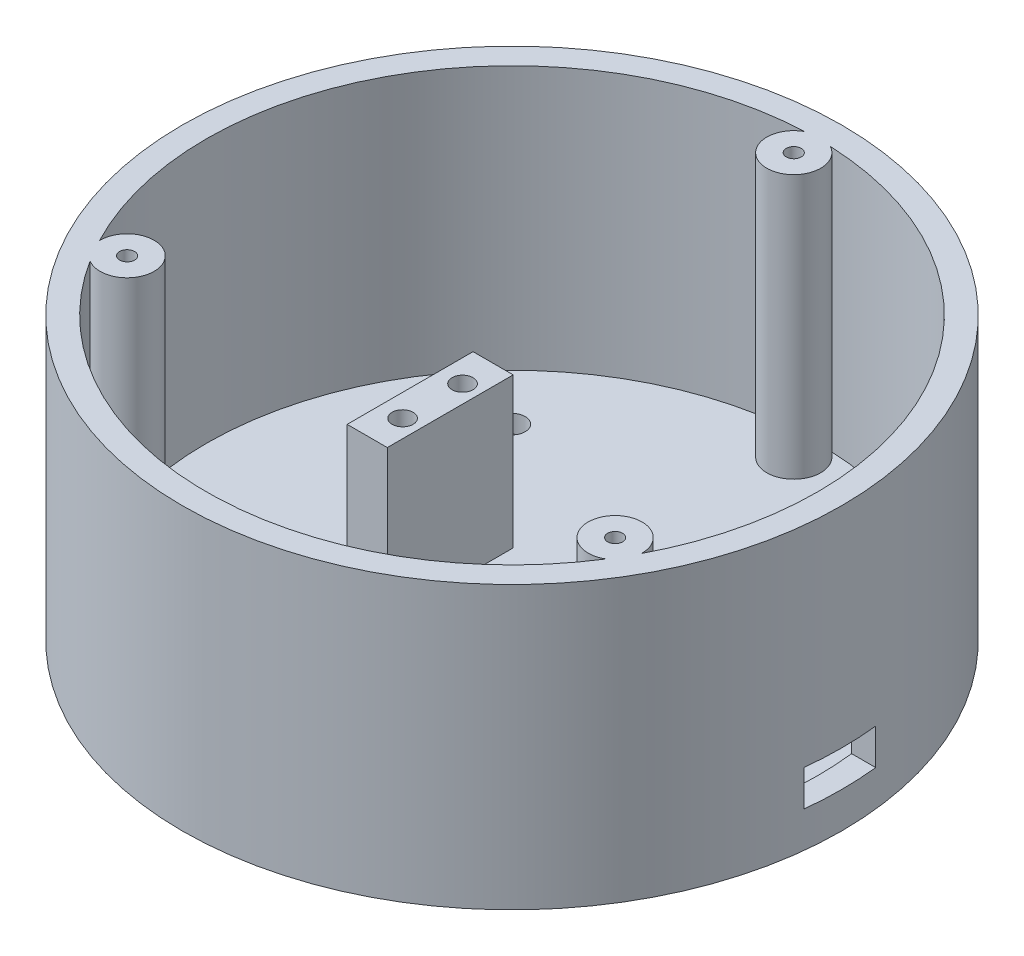
SolidWorks part; units mm, degrees
ref_plane "Piano frontale" through (0, 0, 0) normal (0, 0, 1) x (1, 0, 0)
ref_plane "Piano superiore" through (0, 0, 0) normal (0, 1, 0) x (1, 0, 0)
ref_plane "Piano destro" through (0, 0, 0) normal (1, 0, 0) x (0, 0, -1)
sketch "Schizzo1" plane through (0, 0, 0) normal (0, 1, 0) x (1, 0, 0)
  circle A0 centre (0, 0) radius 55
  dimension "D1" = 110
extrude "Estrusione-Estrusione1" add sketch "Schizzo1" along normal blind 47
sketch "Schizzo2" plane through (0, 47, 0) normal (0, 1, 0) x (1, 0, 0)
  circle A0 centre (0, 0) radius 51
  dimension "D1" = 102
extrude "Taglio-Estrusione1" cut sketch "Schizzo2" against normal blind 44
sketch "Schizzo3" plane through (0, 3, 0) normal (0, 1, 0) x (1, 0, 0)
  line L0 (-13.65, -10.5) -> (-13.65, 10.5) construction
  line L1 (-10.3, 10.5) -> (-17, 10.5)
  line L2 (-10.3, 10.5) -> (-10.3, -10.5)
  line L3 (-10.3, -10.5) -> (-17, -10.5)
  line L4 (-17, 10.5) -> (-17, -10.5)
  line L5 (-10.3, 0) -> (-17, 0) construction
  line L6 (0, -23.6186) -> (0, 49.8842) construction
  line L7 (34.65, 10.5) -> (34.65, -10.5) construction
  line L8 (31.3, 10.5) -> (38, 10.5)
  line L9 (31.3, 10.5) -> (31.3, -10.5)
  line L10 (31.3, -10.5) -> (38, -10.5)
  line L11 (38, 10.5) -> (38, -10.5)
  line L12 (31.3, 0) -> (38, 0) construction
  point P8 (-13.65, 0)
  point P20 (34.65, 0)
  point P21 (0, 49.8842)
  dimension "D1" = 13.65
  dimension "D2" = 6.7
  dimension "D3" = 21
  dimension "D4" = 34.65
  dimension "D5" = 21
  dimension "D6" = 6.7
extrude "Estrusione-Estrusione2" add sketch "Schizzo3" along normal blind 25
sketch "Schizzo9" plane through (0, 28, 0) normal (0, 1, 0) x (1, 0, 0)
  line L0 (0, -14.2526) -> (0, 18.3248) construction
  line L1 (0, 0) -> (-26.1637, 0) construction
  line L3 (0, 0) -> (42.8597, 0) construction
  circle A0 centre (-13.25, 5) radius 1.75
  circle A1 centre (-13.25, -5) radius 1.75
  circle A2 centre (34.25, 5) radius 1.75
  circle A3 centre (34.25, -5) radius 1.75
  point P5 (-13.0819, 0)
  dimension "D2" = 3.5
  dimension "D4" = 3.5
  dimension "D6" = 34.25
  dimension "D1" = 13.25
  dimension "D3" = 5
  dimension "D5" = 5
extrude "Taglio-Estrusione2" cut sketch "Schizzo9" against normal blind 12 contours A2 | A3 | A1 | A0
sketch "Schizzo10" plane through (0, 0, 0) normal (1, 0, 0) x (0, 0, -1)
  line L0 (0, 0) -> (0, 17.9146) construction
  line L1 (-6, 12) -> (6, 12)
  line L2 (-6, 12) -> (-6, 6)
  line L3 (-6, 6) -> (6, 6)
  line L4 (6, 12) -> (6, 6)
  line L5 (-55, 0) -> (55, 0) construction
  dimension "D1" = 12
  dimension "D2" = 6
  dimension "D3" = 6
  dimension "D4" = 6
extrude "Taglio-Estrusione3" cut sketch "Schizzo10" along normal blind 67 from offset 45
sketch "Schizzo12" plane through (0, 3, 0) normal (0, 1, 0) x (1, 0, 0)
  line L0 (0, 0) -> (0, 48.0517) construction
  line L1 (0, 0) -> (-46.6264, 0) construction
  circle A0 centre (-28.28, 28.28) radius 2.2
  circle A1 centre (28.28, 28.28) radius 2.2
  circle A2 centre (28.28, -28.28) radius 2.2
  circle A3 centre (-28.28, -28.28) radius 2.2
  point P14 (0, 0)
  dimension "D1" = 4.4
  dimension "D4" = 4
  dimension "D2" = 28.28
  dimension "D3" = 28.28
  dimension "D5" = 28.28
  dimension "D6" = 56.56
extrude "Taglio-Estrusione4" cut sketch "Schizzo12" against normal through all
sketch "Schizzo13" plane through (0, 3, 0) normal (0, 1, 0) x (1, 0, 0)
  line L0 (0, 0) -> (0, 47) construction
  line L1 (0, 47) -> (0, 57.9267) construction
  line L2 (0, 0) -> (0, -42.5542) construction
  circle A0 centre (0, 47) radius 4.5
  circle A1 centre (40.7032, -23.5) radius 4.5
  circle A2 centre (-40.7032, -23.5) radius 4.5
  point P13 (0, 0)
  dimension "D2" = 9
  dimension "D1" = 47
  dimension "D4" = 81.4064
  dimension "D5" = 40.7032
  dimension "D3" = 3
extrude "Estrusione-Estrusione4" add sketch "Schizzo13" along normal blind 44
sketch "Schizzo14" plane through (0, 47, 0) normal (0, 1, 0) x (1, 0, 0)
  line L0 (0, 0) -> (0, 59.2502) construction
  line L1 (0, 0) -> (0, -42.147) construction
  line L2 (0, 0) -> (-40.7032, 0) construction
  circle A0 centre (0, 47) radius 1.25
  circle A1 centre (40.7032, -23.5) radius 1.25
  circle A2 centre (-40.7032, -23.5) radius 1.25
  arc A4 (-43.0546, -27.3368) -> (-45.2016, -23.618) centre (-40.7032, -23.5) ccw construction
  point P12 (0, 0)
  dimension "D1" = 2.5
  dimension "D5" = 3.25
  dimension "D3" = 40.7032
  dimension "D4" = 23.5
  dimension "D2" = 3
extrude "Taglio-Estrusione6" cut sketch "Schizzo14" against normal blind 12
